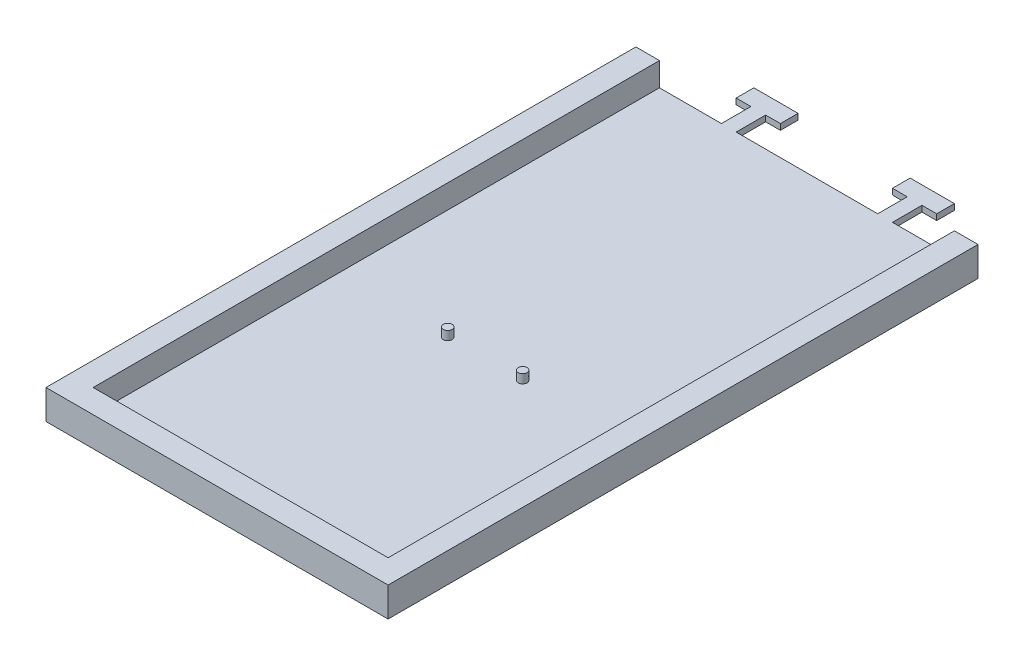
SolidWorks part; units mm, degrees
ref_plane "Front Plane" through (0, 0, 0) normal (0, 0, 1) x (1, 0, 0)
ref_plane "Top Plane" through (0, 0, 0) normal (0, 1, 0) x (1, 0, 0)
ref_plane "Right Plane" through (0, 0, 0) normal (1, 0, 0) x (0, 0, -1)
sketch "Sketch3" plane through (0, 0, 0) normal (0, 1, 0) x (1, 0, 0)
  line L0 (-1156.1049, 777.2674) -> (-1040.1049, 777.2674)
  line L1 (-1040.1049, 777.2674) -> (-1040.1049, 361.2674)
  line L2 (-1040.1049, 361.2674) -> (-1156.1049, 361.2674)
  line L3 (-1156.1049, 361.2674) -> (-1156.1049, 777.2674)
extrude "Boss-Extrude1" add sketch "Sketch3" along normal blind 10
sketch "Sketch4" plane through (0, 10, 0) normal (0, 1, 0) x (1, 0, 0)
  line L4 (-1148.1049, 769.2674) -> (-1048.1049, 769.2674)
  line L5 (-1148.1049, 769.2674) -> (-1148.1049, 369.2674)
  line L6 (-1148.1049, 369.2674) -> (-1048.1049, 369.2674)
  line L7 (-1048.1049, 769.2674) -> (-1048.1049, 369.2674)
  dimension "D1" = 100
  dimension "D2" = 400
extrude "Cut-Extrude1" cut sketch "Sketch4" against normal blind 8
sketch "Sketch6" plane through (0, 2, 0) normal (0, 1, 0) x (1, 0, 0)
  line L1 (-1048.1049, 769.2674) -> (-1148.1049, 769.2674) construction
  line L2 (-1128.1049, 769.2674) -> (-1128.1049, 669.2674)
  line L3 (-1128.1049, 669.2674) -> (-1131.1049, 669.2674)
  line L4 (-1131.1049, 669.2674) -> (-1131.1049, 769.2674)
  line L5 (-1128.1049, 769.2674) -> (-1131.1049, 769.2674)
  line L7 (-1068.1049, 769.2674) -> (-1068.1049, 669.2674)
  line L8 (-1068.1049, 669.2674) -> (-1065.1049, 669.2674)
  line L9 (-1065.1049, 669.2674) -> (-1065.1049, 769.2674)
  line L10 (-1048.1049, 769.2674) -> (-1148.1049, 769.2674) construction
  line L11 (-1068.1049, 769.2674) -> (-1065.1049, 769.2674)
extrude "Boss-Extrude4" add sketch "Sketch6" along normal blind 3
sketch "Sketch7" plane through (0, 2, 0) normal (0, 1, 0) x (1, 0, 0)
  line L0 (-1068.1049, 669.2674) -> (-1085.4049, 669.2674)
  line L1 (-1068.1049, 769.2674) -> (-1068.1049, 669.2674) construction
  line L2 (-1068.1049, 769.2674) -> (-1068.1049, 669.2674) construction
  circle A0 centre (-1085.4049, 452.1683) radius 1.5
extrude "Boss-Extrude5" add sketch "Sketch7" along normal blind 3 contours A0
sketch "Sketch8" plane through (0, 2, 0) normal (0, 1, 0) x (1, 0, 0)
  line L0 (-1040.1049, 777.2674) -> (-1040.1049, 577.2674)
  line L1 (-1040.1049, 361.2674) -> (-1040.1049, 777.2674) construction
  line L2 (-1040.1049, 577.2674) -> (-1156.1049, 577.2674)
  line L3 (-1156.1049, 777.2674) -> (-1156.1049, 361.2674) construction
  line L4 (-1156.1049, 577.2674) -> (-1156.1049, 777.2674)
  line L5 (-1040.1049, 777.2674) -> (-1156.1049, 777.2674) construction
  line L6 (-1156.1049, 777.2674) -> (-1040.1049, 777.2674)
  dimension "D1" = 200
extrude "Cut-Extrude3" cut sketch "Sketch8" against normal blind 10 and the other way blind 10
sketch "Sketch9" plane through (0, 2, 0) normal (0, 1, 0) x (1, 0, 0)
  line L0 (-1156.1049, 561.2674) -> (-1156.1049, 577.2674)
  line L1 (-1127.1049, 561.2674) -> (-1156.1049, 561.2674)
  line L2 (-1079.1049, 577.2674) -> (-1064.1049, 577.2674)
  line L3 (-1156.1049, 577.2674) -> (-1156.1049, 361.2674) construction
  line L4 (-1127.1049, 561.2674) -> (-1127.1049, 571.2674)
  line L5 (-1127.1049, 571.2674) -> (-1132.1049, 571.2674)
  line L6 (-1132.1049, 571.2674) -> (-1132.1049, 577.2674)
  line L7 (-1048.1049, 577.2674) -> (-1148.1049, 577.2674) construction
  line L9 (-1122.1049, 561.2674) -> (-1122.1049, 571.2674)
  line L10 (-1122.1049, 571.2674) -> (-1117.1049, 571.2674)
  line L11 (-1117.1049, 571.2674) -> (-1117.1049, 577.2674)
  line L12 (-1117.1049, 577.2674) -> (-1132.1049, 577.2674)
  line L13 (-1122.1049, 561.2674) -> (-1074.1049, 561.2674)
  line L14 (-1156.1049, 577.2674) -> (-1132.1049, 577.2674)
  line L15 (-1079.1049, 571.2674) -> (-1079.1049, 577.2674)
  line L16 (-1074.1049, 571.2674) -> (-1079.1049, 571.2674)
  line L17 (-1074.1049, 561.2674) -> (-1074.1049, 571.2674)
  line L18 (-1132.1049, 571.2674) -> (-1127.1049, 571.2674)
  line L19 (-1064.1049, 571.2674) -> (-1064.1049, 577.2674)
  line L20 (-1069.1049, 571.2674) -> (-1064.1049, 571.2674)
  line L21 (-1069.1049, 561.2674) -> (-1069.1049, 571.2674)
  line L22 (-1069.1049, 561.2674) -> (-1040.1049, 561.2674)
  line L23 (-1040.1049, 361.2674) -> (-1040.1049, 577.2674) construction
  line L24 (-1127.1049, 561.2674) -> (-1156.1049, 561.2674)
extrude "Cut-Extrude4" cut sketch "Sketch9" against normal blind 10 contours L5 L6 L17 L16 L1 L4 | L14 L0 L1 L16 | L13 L17 L16 L15 L11 L10 L9 | L21 L22 L13 L17 L19 L20
sketch "Sketch11" plane through (0, 10, 0) normal (0, 1, 0) x (1, 0, 0)
  line L0 (-1156.1049, 577.2674) -> (-1148.1049, 577.2674)
  line L1 (-1148.1049, 577.2674) -> (-1148.1049, 561.2674)
  line L2 (-1148.1049, 561.2674) -> (-1156.1049, 561.2674)
  line L3 (-1156.1049, 561.2674) -> (-1156.1049, 577.2674)
  line L4 (-1048.1049, 577.2674) -> (-1040.1049, 577.2674)
  line L5 (-1040.1049, 577.2674) -> (-1040.1049, 561.2674)
  line L6 (-1040.1049, 361.2674) -> (-1040.1049, 577.2674) construction
  line L7 (-1040.1049, 561.2674) -> (-1048.1049, 561.2674)
  line L8 (-1048.1049, 561.2674) -> (-1048.1049, 577.2674)
extrude "Cut-Extrude5" cut sketch "Sketch11" against normal blind 10 contours L3 L0 L1 L2 | L8 L4 L5 L7
sketch "Sketch13" plane through (0, 2, 0) normal (0, 1, 0) x (1, 0, 0)
  line L0 (-1098.1049, 561.2674) -> (-1098.1049, 369.2674)
  line L1 (-1122.1049, 561.2674) -> (-1074.1049, 561.2674) construction
  line L2 (-1148.1049, 369.2674) -> (-1048.1049, 369.2674) construction
  circle A0 centre (-1085.4049, 452.1683) radius 1.5
  circle A1 centre (-1110.8049, 452.1683) radius 1.5
extrude "Boss-Extrude8" add sketch "Sketch13" along normal blind 3 contours A1
